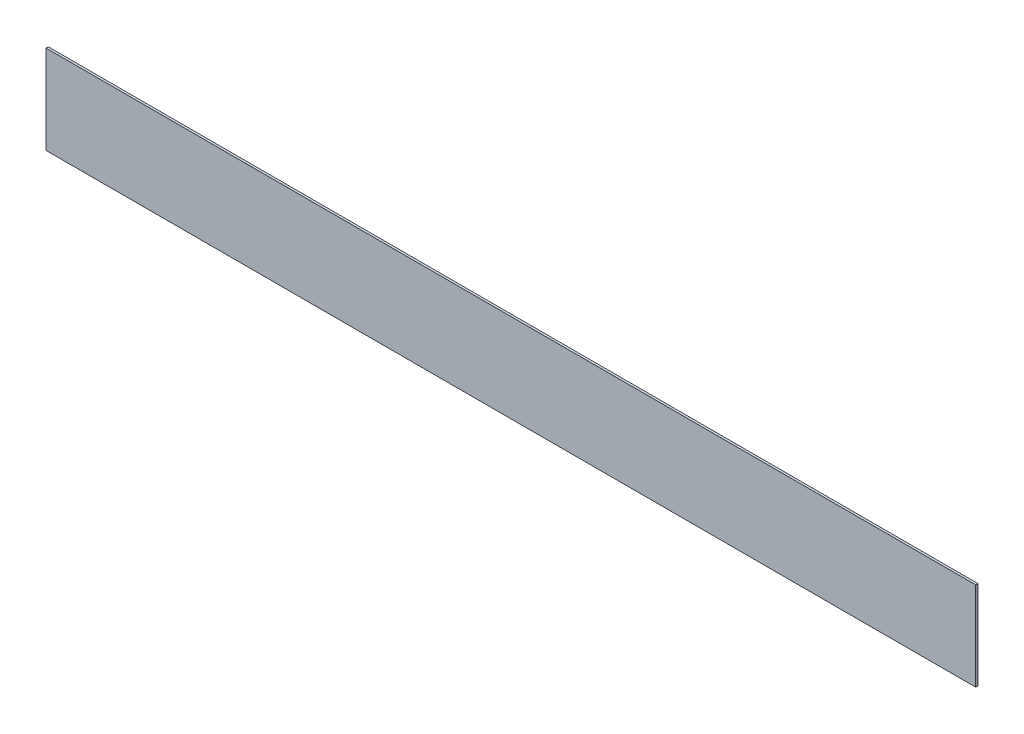
SolidWorks part; units mm, degrees
ref_plane "前视基准面" through (0, 0, 0) normal (0, 0, 1) x (1, 0, 0)
ref_plane "上视基准面" through (0, 0, 0) normal (0, 1, 0) x (1, 0, 0)
ref_plane "右视基准面" through (0, 0, 0) normal (1, 0, 0) x (0, 0, -1)
other "Configuration Table"
sketch "草图1" plane through (0, 0, 0) normal (0, 0, 1) x (1, 0, 0)
  line L1 (0, 0) -> (2056, 0)
  line L2 (0, 0) -> (0, 196)
  line L3 (0, 196) -> (2056, 196)
  line L4 (2056, 0) -> (2056, 196)
  dimension "D1" = 196
  dimension "D2" = 2056
extrude "凸台-拉伸1" add sketch "草图1" along normal blind 5
